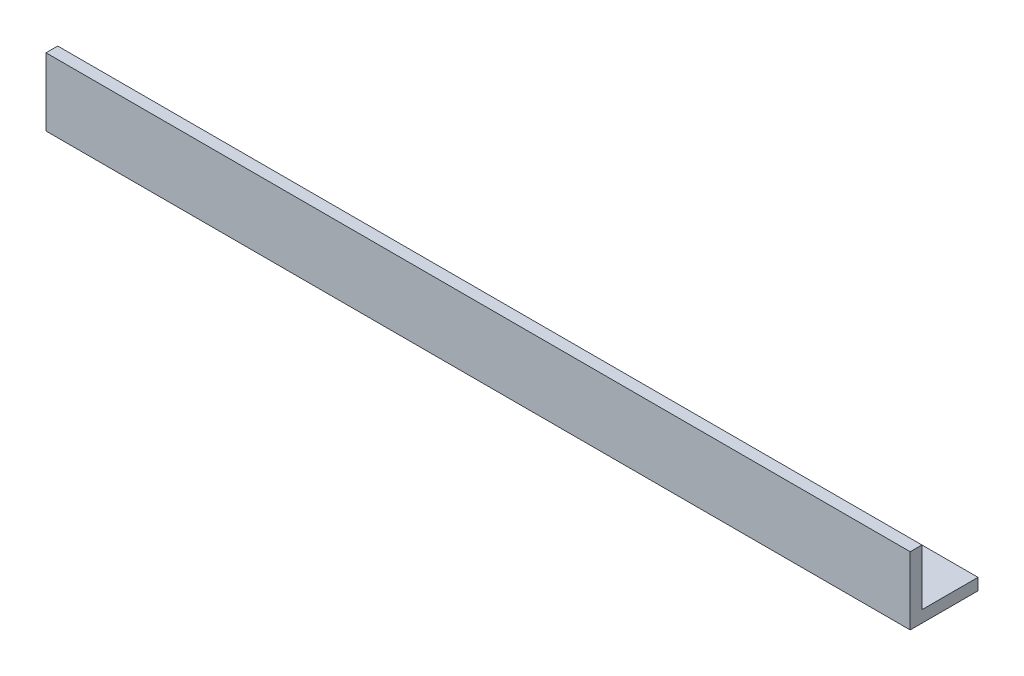
SolidWorks part; units mm, degrees
ref_plane "Front Plane" through (0, 0, 0) normal (0, 0, 1) x (1, 0, 0)
ref_plane "Top Plane" through (0, 0, 0) normal (0, 1, 0) x (1, 0, 0)
ref_plane "Right Plane" through (0, 0, 0) normal (1, 0, 0) x (0, 0, -1)
sketch "Sketch1" plane through (0, 0, 0) normal (1, 0, 0) x (0, 0, -1)
  line L0 (0, 0) -> (20, 0)
  line L1 (20, 0) -> (20, 3.4612)
  line L2 (20, 3.4612) -> (3.4612, 3.4612)
  line L3 (3.4612, 3.4612) -> (3.4612, 20)
  line L4 (3.4612, 20) -> (0, 20)
  line L5 (0, 20) -> (0, 0)
  dimension "D1" = 3.4612
  dimension "D2" = 20
extrude "Boss-Extrude1" add sketch "Sketch1" along normal blind 255
